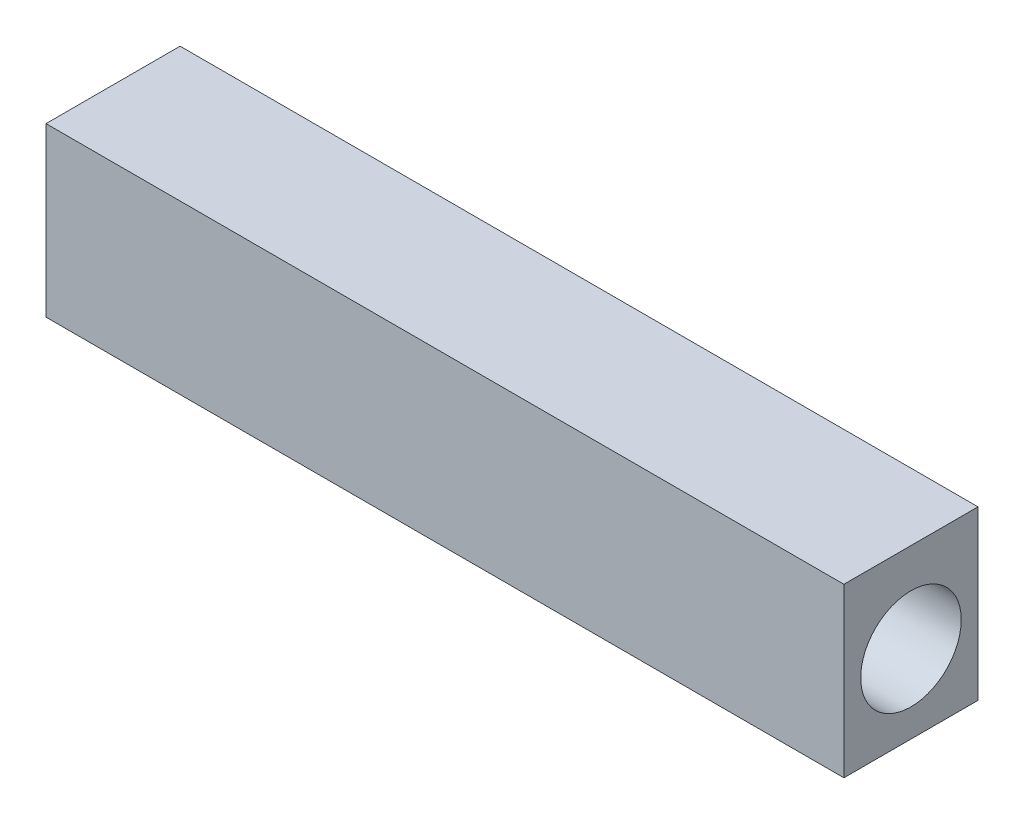
SolidWorks part; units mm, degrees
ref_plane "前基準面" through (0, 0, 0) normal (0, 0, 1) x (1, 0, 0)
ref_plane "上基準面" through (0, 0, 0) normal (0, 1, 0) x (1, 0, 0)
ref_plane "右基準面" through (0, 0, 0) normal (1, 0, 0) x (0, 0, -1)
sketch "草圖1" plane through (0, 0, 0) normal (0, 1, 0) x (1, 0, 0)
  line L1 (-16.2, 6) -> (16.2, 6)
  line L2 (-16.2, 6) -> (-16.2, -6)
  line L3 (-16.2, -6) -> (16.2, -6)
  line L4 (16.2, 6) -> (16.2, -6)
  line L5 (-16.2, 6) -> (16.2, -6) construction
  line L6 (-16.2, -6) -> (16.2, 6) construction
  point P0 (0, 0)
  dimension "D1" = 32.4
  dimension "D2" = 12
extrude "填料-伸長1" add sketch "草圖1" along normal blind 10
sketch "草圖3" plane through (-16.2, 0, 0) normal (-1, 0, 0) x (0, 0, 1)
  line L0 (0, -1000) -> (0, 49000) construction
  line L1 (-6, 10) -> (6, 10) construction
  line L2 (0, 10) -> (-1.142, 10) construction
  line L3 (0, 10) -> (0, 7) construction
  line L4 (0, 7) -> (-1.142, 7) construction
  line L5 (-1.142, 10) -> (-1.142, 7) construction
  line L6 (-1001.142, 7) -> (48998.858, 7) construction
  dimension "D1" = 3
sketch "草圖4" plane through (-16.2, 0, 0) normal (-1, 0, 0) x (0, 0, 1)
  circle A0 centre (0, 7) radius 4
  dimension "D1" = 8
extrude "除料-伸長2" cut sketch "草圖4" against normal blind 8.5
ref_plane "平面2" through (-16.2, 0, 0) normal (-1, 0, 0) x (0, 0, 1)
sketch "草圖6" plane through (-16.2, 0, 0) normal (-1, 0, 0) x (0, 0, 1)
  circle A0 centre (0, 7) radius 4
curve "螺旋曲線/渦捲線2" pitch 0.4054 height 8.5135 turns 21
sketch "草圖7" plane through (-7.7, 0, 0) normal (-1, 0, 0) x (0, 0, 1)
  circle A0 centre (0, 7) radius 3.4
  dimension "D1" = 6.8
extrude "除料-伸長3" cut sketch "草圖7" against normal blind 7.9
sketch "草圖8" plane through (16.2, 0, 0) normal (1, 0, 0) x (0, 0, -1)
  circle A0 centre (0, 7) radius 4.5
  dimension "D1" = 9
extrude "除料-伸長4" cut sketch "草圖8" against normal blind 16
sketch "草圖9" plane through (0, 10, 0) normal (0, 1, 0) x (1, 0, 0)
  line L0 (-16.2, 201001.142) -> (-16.2, -248998.858) construction
  line L1 (-16.2, 6) -> (16.2, 6)
  line L2 (-16.2, 6) -> (-16.2, 3.3541)
  line L3 (-16.2, 3.3541) -> (16.2, 3.3541)
  line L4 (16.2, 6) -> (16.2, 3.3541)
  line L5 (16.2, 6) -> (-16.2, 6) construction
extrude "填料-伸長2" add sketch "草圖9" along normal blind 5
sketch "草圖10" plane through (0, 10, 0) normal (0, 1, 0) x (1, 0, 0)
  line L0 (-16.2, 3.3725) -> (-16.2, 2.6855)
  line L1 (-16.2, 201001.142) -> (-16.2, -248998.858) construction
  line L2 (-16.2, 2.6855) -> (-7.7, 2.6458)
  line L3 (-7.7, 2.6458) -> (-7.7, 1.6)
  line L4 (-7.7, 4) -> (-7.7, -4) construction
  line L5 (-7.7, 3.4) -> (-7.7, -3.4) construction
  line L6 (-7.7, 1.6) -> (0.2, 1.6)
  line L7 (0.2, -4.5) -> (0.2, 4.5) construction
  line L8 (0.2, 1.6) -> (-7.7, 1.6) construction
  line L9 (0.2, 1.6) -> (0.2, 3.3541)
  line L10 (0.2, 3.3541) -> (-16.2, 3.3725)
extrude "填料-伸長3" add sketch "草圖10" along normal blind 5
sketch "草圖11" plane through (0, 10, 0) normal (0, 1, 0) x (1, 0, 0)
  line L0 (-16.2, -2.6607) -> (-16.2, -6)
  line L1 (-16.2, 201001.142) -> (-16.2, -248998.858) construction
  line L2 (-16.2, -6) -> (16.2, -6) construction
  line L3 (-16.2, -6) -> (16.2, -6)
  line L4 (16.2, -6) -> (16.2, -3.3541)
  line L5 (16.2, -3.3541) -> (0.2, -3.3541)
  line L6 (0.2, -3.3541) -> (0.2, -1.6)
  line L7 (0.2, -1.6) -> (-7.7, -1.6)
  line L8 (-7.7, -1.6) -> (-7.7, -2.6458)
  line L9 (-7.7, -2.6458) -> (-16.2, -2.6607)
extrude "填料-伸長4" add sketch "草圖11" along normal blind 5
sketch "草圖12" plane through (-16.2, 0, 0) normal (-1, 0, 0) x (0, 0, 1)
  line L0 (-6, 15) -> (-6, 0) construction
  line L1 (-6, 10) -> (6, 10)
  line L2 (-6, 10) -> (-6, 15)
  line L3 (-6, 15) -> (6, 15)
  line L4 (6, 10) -> (6, 15)
extrude "填料-伸長5" add sketch "草圖12" against normal through all
sketch "草圖13" plane through (-16.2, 0, 0) normal (-1, 0, 0) x (0, 0, 1)
  circle A0 centre (0, 7) radius 4
extrude "除料-伸長5" cut sketch "草圖13" against normal blind 8.5
sketch "草圖14" plane through (-7.7, 0, 0) normal (-1, 0, 0) x (0, 0, 1)
  circle A0 centre (0, 7) radius 3.4
extrude "除料-伸長6" cut sketch "草圖14" against normal blind 7.9
sketch "草圖15" plane through (16.2, 0, 0) normal (1, 0, 0) x (0, 0, -1)
  circle A0 centre (0, 7) radius 4.5
extrude "除料-伸長8" cut sketch "草圖15" against normal blind 16
sketch "草圖16" plane through (16.2, 0, 0) normal (1, 0, 0) x (0, 0, -1)
  line L1 (6, 15) -> (-6, 15)
  line L2 (6, 15) -> (6, 0)
  line L3 (6, 0) -> (-6, 0)
  line L4 (-6, 15) -> (-6, 0)
extrude "填料-伸長8" add sketch "草圖16" along normal blind 39
sketch "草圖17" plane through (55.2, 0, 0) normal (1, 0, 0) x (0, 0, -1)
  circle A0 centre (0, 7) radius 4.5
  dimension "D1" = 9
extrude "除料-伸長9" cut sketch "草圖17" against normal blind 39
